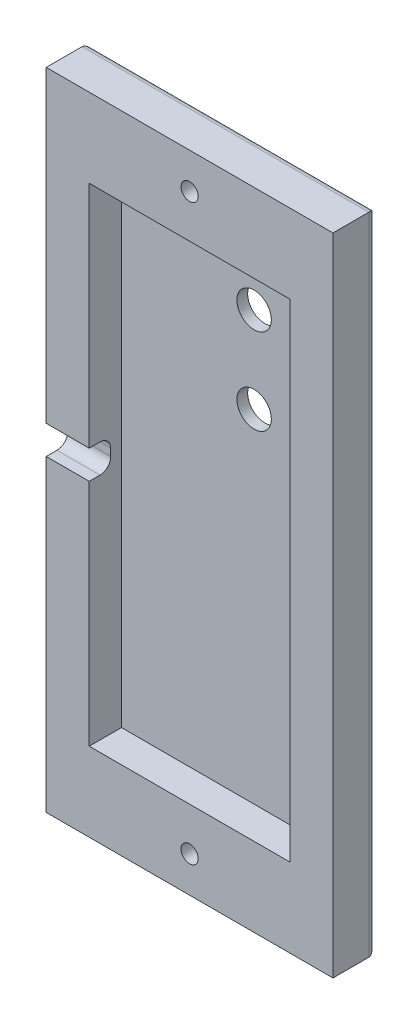
SolidWorks part; units mm, degrees
ref_plane "Front Plane" through (0, 0, 0) normal (1, 0, 0) x (0, 1, 0)
ref_plane "Top Plane" through (0, 0, 0) normal (0, 0, 1) x (0, 1, 0)
ref_plane "Right Plane" through (0, 0, 0) normal (0, 1, 0) x (-1, 0, 0)
sketch "Sketch1" plane through (0, 0, 0) normal (0, 0, 1) x (0, 1, 0)
  line L1 (0, 0) -> (90, 0)
  line L2 (0, 0) -> (0, 40)
  line L3 (0, 40) -> (90, 40)
  line L4 (90, 0) -> (90, 40)
  dimension "D1" = 40
  dimension "D2" = 90
extrude "Boss-Extrude1" add sketch "Sketch1" along normal blind 6
sketch "Sketch2" plane through (0, 0, 6) normal (0, 0, 1) x (1, 0, 0)
  line L0 (-20, 90) -> (-20, 0) construction
  line L1 (0, 90) -> (-40, 90) construction
  line L2 (-40, 0) -> (0, 0) construction
  line L3 (-34, 79) -> (-34, 11)
  line L4 (-34, 79) -> (-6, 79)
  line L5 (-34, 11) -> (-6, 11)
  line L6 (-6, 79) -> (-6, 11)
  line L7 (-34, 79) -> (-6, 11) construction
  line L8 (-34, 11) -> (-6, 79) construction
  point P6 (-20, 45)
  point P7 (-20, 45)
  dimension "D1" = 28
  dimension "D2" = 68
extrude "Cut-Extrude1" cut sketch "Sketch2" against normal blind 4.5
sketch "Sketch6" plane through (0, 0, 6) normal (0, 0, 1) x (1, 0, 0)
  line L0 (0, 90) -> (-40, 90) construction
  line L1 (-40, 90) -> (-40, 0) construction
  circle A0 centre (-20, 85) radius 1.2
  dimension "D1" = 2.4
  dimension "D2" = 5
  dimension "D3" = 20
extrude "Cut-Extrude5" cut sketch "Sketch6" against normal through all
sketch "Sketch7" plane through (0, 0, 6) normal (0, 0, 1) x (1, 0, 0)
  line L0 (-40, 0) -> (0, 0) construction
  line L1 (-40, 90) -> (-40, 0) construction
  circle A0 centre (-20, 5) radius 1.2
  point P6 (-31.3928, 1.0841)
  point P9 (-40.304, 4.467)
  dimension "D1" = 2.4
  dimension "D2" = 5
  dimension "D3" = 20
extrude "Cut-Extrude6" cut sketch "Sketch7" against normal through all
sketch "Sketch8" plane through (0, 0, 1.5) normal (0, 0, 1) x (1, 0, 0)
  line L0 (-15.5, 79) -> (-15.5, 11) construction
  line L1 (-6, 79) -> (-34, 79) construction
  line L2 (-34, 11) -> (-6, 11) construction
  line L4 (-6, 79) -> (-34, 79) construction
  line L5 (-6, 11) -> (-6, 79) construction
  circle A0 centre (-15.5, 70.7) radius 2.4
  circle A1 centre (-15.5, 58.7) radius 2.4
  dimension "D2" = 4.8
  dimension "D1" = 9.5
  dimension "D3" = 8.3
  dimension "D4" = 12
extrude "Cut-Extrude7" cut sketch "Sketch8" against normal through all
sketch "Sketch9" plane through (0, 0, 0) normal (0, 0, -1) x (1, 0, 0)
  circle A0 centre (-20, -5) radius 2.15
  circle A1 centre (-20, -85) radius 2.15
  dimension "D1" = 4.3
extrude "Cut-Extrude8" cut sketch "Sketch9" against normal blind 2.4
fillet "Fillet3" radius 1 4 edges at (-20, 90, 0) (0, 45, 0) (-40, 45, 0) (-20, 0, 0)
sketch "Sketch10" plane through (-40, 0, 0) normal (-1, 0, 0) x (0, -1, 0)
  line L0 (-90, 6) -> (0, 6) construction
  line L1 (-47, 6) -> (-43, 6)
  line L2 (-47, 6) -> (-47, 3)
  line L3 (-47, 3) -> (-43, 3)
  line L4 (-43, 6) -> (-43, 3)
  line L5 (-90, 6) -> (-90, 1) construction
  line L6 (0, 6) -> (0, 1) construction
  dimension "D1" = 43
  dimension "D2" = 43
  dimension "D3" = 3
extrude "Cut-Extrude9" cut sketch "Sketch10" against normal blind 10
fillet "Fillet4" radius 1.5 2 edges at (-37, 43, 3) (-37, 47, 3)
